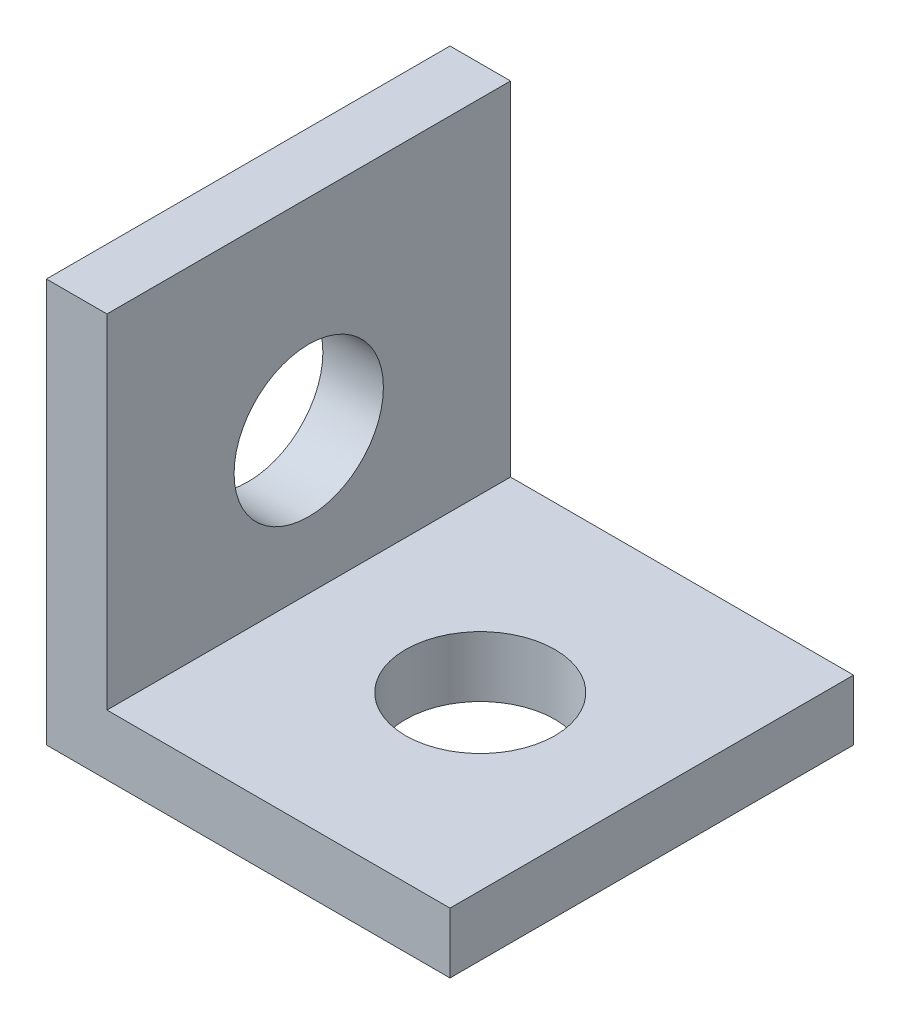
SolidWorks part; units mm, degrees
ref_plane "Front Plane" through (0, 0, 0) normal (0, 0, 1) x (1, 0, 0)
ref_plane "Top Plane" through (0, 0, 0) normal (0, 1, 0) x (1, 0, 0)
ref_plane "Right Plane" through (0, 0, 0) normal (1, 0, 0) x (0, 0, -1)
sketch "Sketch1" plane through (0, 0, 0) normal (0, 0, 1) x (1, 0, 0)
  line L0 (1.5, -10) -> (18.5, -10)
  line L1 (-1.5, -10) -> (1.5, -10)
  line L2 (-1.5, -10) -> (-1.5, 10)
  line L3 (-1.5, 10) -> (1.5, 10)
  line L4 (1.5, -7) -> (1.5, 10)
  line L5 (-1.5, -10) -> (1.5, 10) construction
  line L6 (-1.5, 10) -> (1.5, -10) construction
  line L7 (18.5, -10) -> (18.5, -7)
  line L8 (18.5, -7) -> (1.5, -7)
  point P0 (0, 0)
  dimension "D1" = 3
  dimension "D2" = 20
  dimension "D3" = 17
  dimension "D4" = 3
extrude "Boss-Extrude1" add sketch "Sketch1" along normal blind 20
sketch "Sketch2" plane through (0, -7, 0) normal (0, 1, 0) x (1, 0, 0)
  circle A0 centre (10, -10) radius 3.7
  dimension "D1" = 7.4
extrude "Cut-Extrude1" cut sketch "Sketch2" against normal blind 20
sketch "Sketch3" plane through (1.5, 0, 0) normal (1, 0, 0) x (0, 0, -1)
  circle A0 centre (-10, 0) radius 3.7
  dimension "D1" = 7.4
extrude "Cut-Extrude2" cut sketch "Sketch3" against normal blind 20
